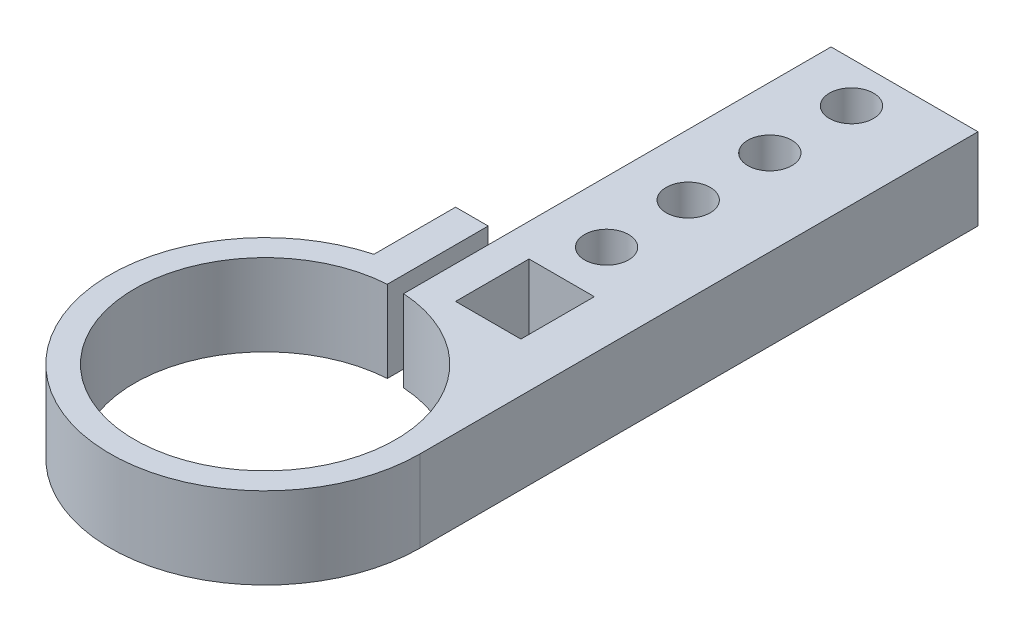
SolidWorks part; units mm, degrees
ref_plane "Front Plane" through (0, 0, 0) normal (0, 0, 1) x (1, 0, 0)
ref_plane "Top Plane" through (0, 0, 0) normal (0, 1, 0) x (1, 0, 0)
ref_plane "Right Plane" through (0, 0, 0) normal (1, 0, 0) x (0, 0, -1)
sketch "Sketch1" plane through (0, 0, 0) normal (0, 1, 0) x (1, 0, 0)
  circle A0 centre (0, 0) radius 20.32
  circle A1 centre (0, 0) radius 24.13
  dimension "D1" = 40.64
  dimension "D2" = 48.26
extrude "Boss-Extrude1" add sketch "Sketch1" along normal blind 12.7
sketch "Sketch2" plane through (0, 0, 0) normal (0, 1, 0) x (1, 0, 0)
  line L1 (6.35, 35.9795) -> (-6.35, 35.9795)
  line L2 (6.35, 35.9795) -> (6.35, 23.2795)
  line L3 (6.35, 23.2795) -> (-6.35, 23.2795)
  line L4 (-6.35, 35.9795) -> (-6.35, 23.2795)
  line L5 (6.35, 35.9795) -> (-6.35, 23.2795) construction
  line L6 (6.35, 23.2795) -> (-6.35, 35.9795) construction
  circle A0 centre (0, 0) radius 24.13 construction
  point P0 (0, 29.6295)
  dimension "D1" = 12.7
  dimension "D2" = 12.7
extrude "Boss-Extrude2" add sketch "Sketch2" along normal blind 12.7
sketch "Sketch4" plane through (0, 0, 0) normal (0, 1, 0) x (1, 0, 0)
  line L1 (-1.27, 1.4316) -> (1.27, 1.4316)
  line L2 (-1.27, 1.4316) -> (-1.27, 60.42)
  line L3 (-1.27, 60.42) -> (1.27, 60.42)
  line L4 (1.27, 1.4316) -> (1.27, 60.42)
  line L5 (-1.27, 1.4316) -> (1.27, 60.42) construction
  line L6 (-1.27, 60.42) -> (1.27, 1.4316) construction
  point P0 (0, 30.9258)
  point P5 (0, 0)
  dimension "D1" = 2.54
extrude "Cut-Extrude2" cut sketch "Sketch4" along normal through all
sketch "Sketch5" plane through (6.35, 0, 0) normal (1, 0, 0) x (0, 0, -1)
  line L1 (35.9795, 12.7) -> (0, 12.7)
  line L2 (35.9795, 12.7) -> (35.9795, 0)
  line L3 (35.9795, 0) -> (0, 0)
  line L4 (0, 12.7) -> (0, 0)
extrude "Boss-Extrude3" add sketch "Sketch5" against normal up to next from offset 17.78
sketch "Sketch6" plane through (0, 12.7, 0) normal (0, 1, 0) x (1, 0, 0)
  line L0 (1.27, 20.2803) -> (1.27, 35.9795) construction
  line L1 (24.13, 35.9795) -> (1.27, 35.9795)
  line L2 (24.13, 35.9795) -> (24.13, 86.7795)
  line L3 (24.13, 86.7795) -> (1.27, 86.7795)
  line L4 (1.27, 35.9795) -> (1.27, 86.7795)
  dimension "D1" = 50.8
extrude "Boss-Extrude4" add sketch "Sketch6" against normal blind 12.7
sketch "Sketch7" plane through (0, 0, 0) normal (0, 1, 0) x (1, 0, 0)
  line L0 (24.13, 86.7795) -> (1.27, 86.7795) construction
  line L2 (1.27, 20.2803) -> (1.27, 86.7795) construction
  line L4 (6.35, 34.7095) -> (16.51, 34.7095)
  line L5 (6.35, 34.7095) -> (6.35, 23.2795)
  line L6 (6.35, 23.2795) -> (16.51, 23.2795)
  line L7 (16.51, 34.7095) -> (16.51, 23.2795)
  circle A0 centre (10.795, 80.4295) radius 3.429
  circle A1 centre (36.195, 80.4295) radius 3.429
  circle A2 centre (36.195, 67.7295) radius 3.429
  circle A3 centre (10.795, 67.7295) radius 3.429
  circle A4 centre (10.795, 55.0295) radius 3.429
  circle A5 centre (36.195, 55.0295) radius 3.429
  circle A6 centre (10.795, 42.3295) radius 3.429
  circle A7 centre (36.195, 42.3295) radius 3.429
  dimension "D1" = 6.858
  dimension "D9" = 12.7
  dimension "D2" = 6.35
  dimension "D3" = 9.525
  dimension "D6" = 11.43
  dimension "D7" = 5.08
  dimension "D8" = 10.16
  dimension "D4" = 2
  dimension "D5" = 4
extrude "Cut-Extrude3" cut sketch "Sketch7" along normal through all
